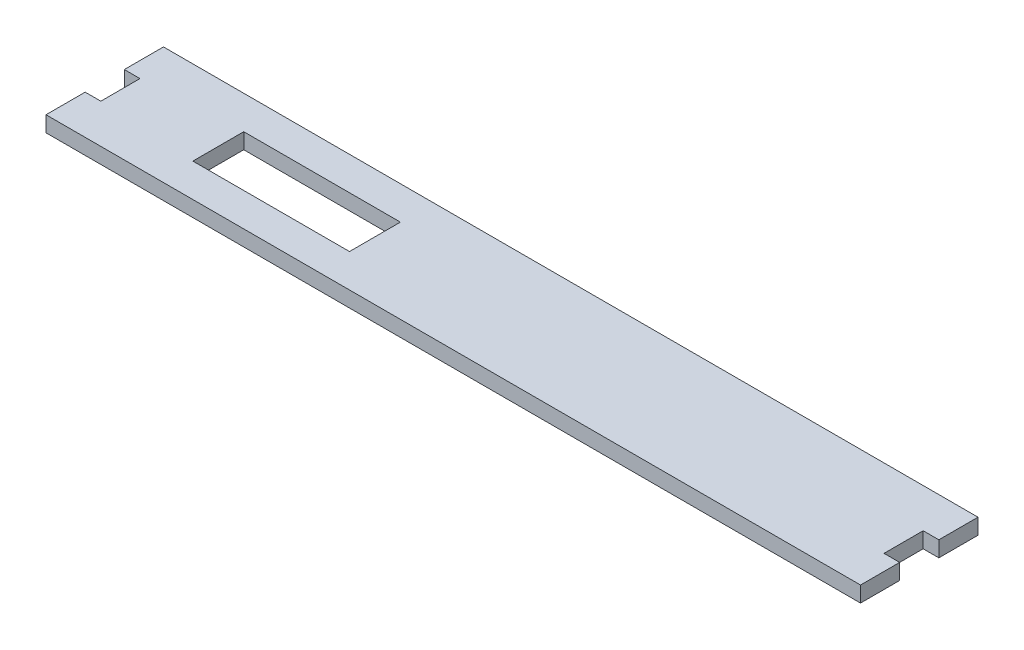
SolidWorks part; units mm, degrees
ref_plane "Front Plane" through (0, 0, 0) normal (0, 0, 1) x (1, 0, 0)
ref_plane "Top Plane" through (0, 0, 0) normal (0, 1, 0) x (1, 0, 0)
ref_plane "Right Plane" through (0, 0, 0) normal (1, 0, 0) x (0, 0, -1)
sketch "Sketch1" plane through (0, 0, 0) normal (0, 1, 0) x (1, 0, 0)
  line L1 (0, 0) -> (200, 0)
  line L2 (0, 0) -> (0, 30)
  line L3 (0, 30) -> (200, 30)
  line L4 (200, 0) -> (200, 30)
  line L5 (0, 0) -> (-4, 0)
  line L6 (0, 0) -> (0, 10)
  line L7 (0, 10) -> (-4, 10)
  line L8 (-4, 0) -> (-4, 10)
  line L9 (0, 30) -> (-4, 30)
  line L10 (0, 30) -> (0, 20)
  line L11 (0, 20) -> (-4, 20)
  line L12 (-4, 30) -> (-4, 20)
  line L13 (200, 0) -> (204, 0)
  line L14 (200, 0) -> (200, 10)
  line L15 (200, 10) -> (204, 10)
  line L16 (204, 0) -> (204, 10)
  line L17 (200, 30) -> (204, 30)
  line L18 (200, 30) -> (200, 20)
  line L19 (200, 20) -> (204, 20)
  line L20 (204, 30) -> (204, 20)
  line L21 (25, 21.5) -> (65, 21.5)
  line L22 (25, 21.5) -> (25, 8.5)
  line L23 (25, 8.5) -> (65, 8.5)
  line L24 (65, 21.5) -> (65, 8.5)
  dimension "D1" = 200
  dimension "D2" = 30
  dimension "D3" = 10
  dimension "D4" = 10
  dimension "D5" = 4
  dimension "D6" = 4
  dimension "D7" = 10
  dimension "D8" = 10
  dimension "D9" = 4
  dimension "D10" = 4
  dimension "D11" = 40
  dimension "D12" = 13
  dimension "D13" = 8.5
  dimension "D14" = 25
extrude "Boss-Extrude1" add sketch "Sketch1" along normal blind 4 contours L1 L4 L3 L2 L21 L24 L23 L22 | L8 L5 L2 L7 | L9 L12 L11 L2 | L20 L17 L4 L19 | L13 L16 L15 L14
